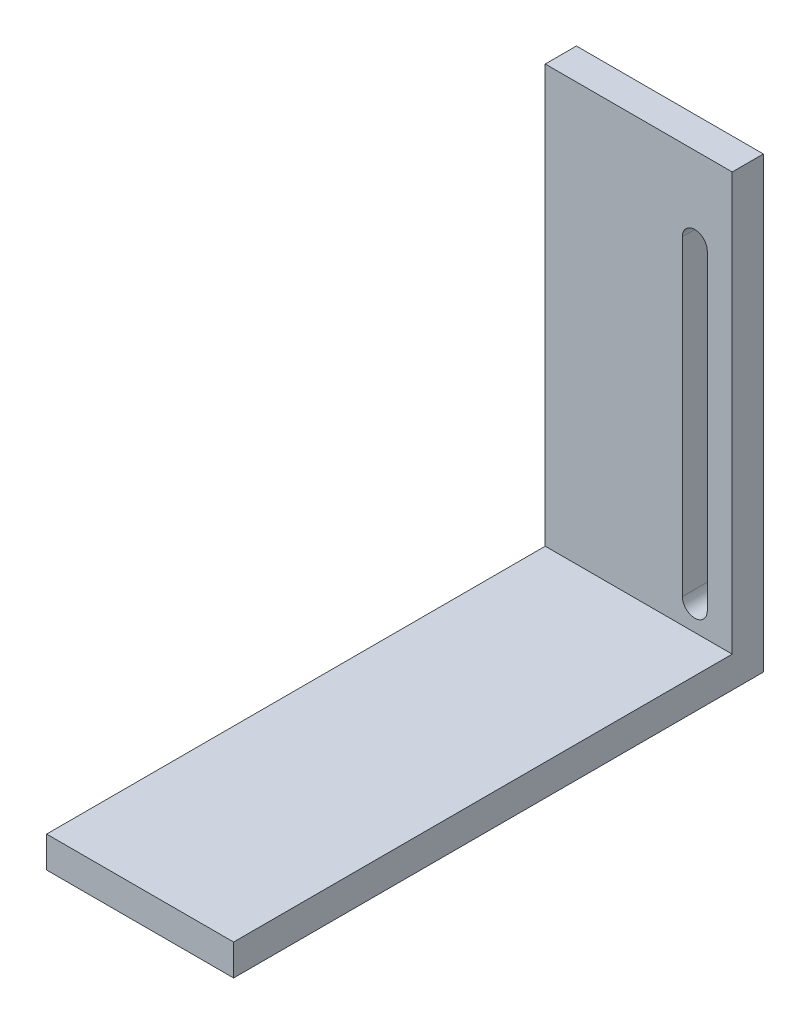
SolidWorks part; units mm, degrees
ref_plane "Front Plane" through (0, 0, 0) normal (0, 0, 1) x (1, 0, 0)
ref_plane "Top Plane" through (0, 0, 0) normal (0, 1, 0) x (1, 0, 0)
ref_plane "Right Plane" through (0, 0, 0) normal (1, 0, 0) x (0, 0, -1)
sketch "Sketch1" plane through (0, 0, 0) normal (0, 0, 1) x (1, 0, 0)
  line L0 (30.48, 74.93) -> (30.48, 11.43) construction
  line L1 (0, 0) -> (38.1, 0)
  line L2 (0, 0) -> (0, 91.44)
  line L3 (0, 91.44) -> (38.1, 91.44)
  line L4 (38.1, 0) -> (38.1, 91.44)
  line L5 (33.02, 74.93) -> (33.02, 11.43)
  line L6 (27.94, 74.93) -> (27.94, 11.43)
  arc A0 (33.02, 74.93) -> (27.94, 74.93) centre (30.48, 74.93) ccw
  arc A1 (27.94, 11.43) -> (33.02, 11.43) centre (30.48, 11.43) ccw
  point P7 (30.48, 43.18)
  dimension "D3" = 2.54
  dimension "D4" = 11.43
  dimension "D1" = 38.1
  dimension "D2" = 91.44
  dimension "D5" = 7.62
  dimension "D6" = 63.5
  dimension "D7" = 30.48
extrude "Boss-Extrude1" add sketch "Sketch1" along normal blind 6.35
sketch "Sketch2" plane through (0, 0, 6.35) normal (0, 0, 1) x (1, 0, 0)
  line L0 (38.1, 0) -> (38.1, 91.44) construction
  line L1 (0, 0) -> (38.1, 0)
  line L2 (0, 0) -> (0, 6.35)
  line L3 (0, 6.35) -> (38.1, 6.35)
  line L4 (38.1, 0) -> (38.1, 6.35)
  dimension "D1" = 6.35
extrude "Boss-Extrude2" add sketch "Sketch2" along normal blind 101.6
